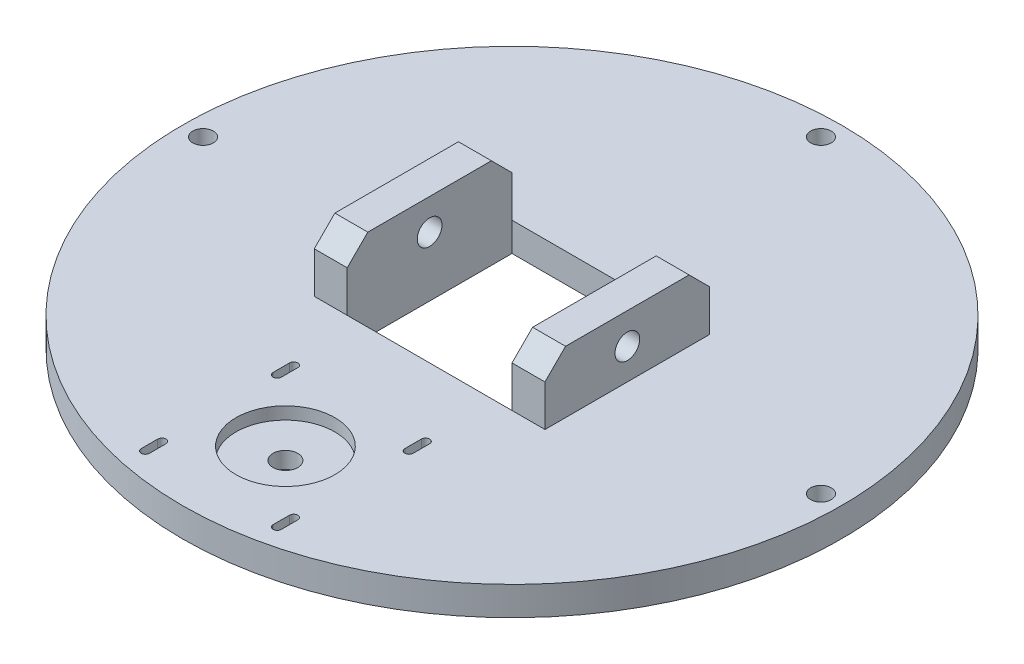
SolidWorks part; units mm, degrees
ref_plane "Front Plane" through (0, 0, 0) normal (0, 0, 1) x (1, 0, 0)
ref_plane "Top Plane" through (0, 0, 0) normal (0, 1, 0) x (1, 0, 0)
ref_plane "Right Plane" through (0, 0, 0) normal (1, 0, 0) x (0, 0, -1)
sketch "Sketch1" plane through (0, 0, 0) normal (0, 1, 0) x (1, 0, 0)
  circle A0 centre (0, 0) radius 80
  dimension "D1" = 160
extrude "Boss-Extrude1" add sketch "Sketch1" along normal blind 7 contours A0
sketch "Sketch2" plane through (0, 7, 0) normal (0, 1, 0) x (1, 0, 0)
  circle A0 centre (0, 0) radius 75 construction
  circle A1 centre (-75, 0) radius 2.5
  circle A2 centre (0, 75) radius 2.5
  circle A3 centre (75, 0) radius 2.5
  point P3 (0, 75)
  point P4 (75, 0)
  point P5 (0, -75)
  point P6 (-75, 0)
  point P7 (-75, 0)
  dimension "D1" = 150
extrude "Cut-Extrude1" cut sketch "Sketch2" against normal up to next
sketch "Sketch3" plane through (0, 7, 0) normal (0, 1, 0) x (1, 0, 0)
  line L1 (-20, 20) -> (20, 20)
  line L2 (-20, 20) -> (-20, -20)
  line L3 (-20, -20) -> (20, -20)
  line L4 (20, 20) -> (20, -20)
  dimension "D1" = 40
  dimension "D2" = 20
  dimension "D3" = 20
extrude "Cut-Extrude2" cut sketch "Sketch3" against normal up to next
sketch "Sketch5" plane through (0, 7, 0) normal (0, 1, 0) x (1, 0, 0)
  line L0 (-20, -20) -> (20, -20) construction
  line L1 (-20, 20) -> (-28, 20)
  line L2 (-20, 20) -> (-20, -20)
  line L3 (-20, -20) -> (-28, -20)
  line L4 (-28, 20) -> (-28, -20)
  dimension "D1" = 8
extrude "Boss-Extrude2" add sketch "Sketch5" along normal blind 15
fillet "Fillet1" radius 5 2 edges at (-24, 22, -20) (-24, 22, 20) profile chamfer
sketch "Sketch6" plane through (-28, 0, 0) normal (-1, 0, 0) x (0, 0, 1)
  line L0 (-15, 22) -> (15, 22) construction
  line L2 (20, 17) -> (20, 7) construction
  circle A0 centre (0, 14.5) radius 3
  dimension "D1" = 6
  dimension "D2" = 7.5
  dimension "D3" = 20
extrude "Cut-Extrude4" cut sketch "Sketch6" against normal up to next
ref_plane "Plane1" [suppressed] through (0, 0, 0) normal (-1, 0, 0) x (0, 0, 1)
mirror "Mirror1" about plane through (0, 0, 0) normal (-1, 0, 0) of "Cut-Extrude4", "Fillet1", "Boss-Extrude2"
sketch "Sketch4" plane through (0, 7, 0) normal (0, 1, 0) x (1, 0, 0)
  line L0 (-16, -41) -> (-16, -37) construction
  line L5 (-21, -34) -> (21, -34) construction
  line L6 (0, 0) -> (0, -80) construction
  line L7 (0, 0) -> (-72.5, 0) construction
  line L8 (-21, -34) -> (-21, -76) construction
  line L23 (-21, -76) -> (21, -76) construction
  line L24 (21, -34) -> (21, -76) construction
  line L27 (-16, -39) -> (16, -39) construction
  line L28 (-16, -39) -> (-16, -71) construction
  line L31 (-16, -71) -> (16, -71) construction
  line L32 (16, -39) -> (16, -71) construction
  line L33 (-17, -41) -> (-17, -37)
  line L34 (-15, -41) -> (-15, -37)
  line L35 (16, -41) -> (16, -37) construction
  line L36 (15, -41) -> (15, -37)
  line L37 (17, -41) -> (17, -37)
  line L38 (16, -73) -> (16, -69) construction
  line L39 (15, -73) -> (15, -69)
  line L40 (17, -73) -> (17, -69)
  line L41 (-16, -73) -> (-16, -69) construction
  line L42 (-17, -73) -> (-17, -69)
  line L43 (-15, -73) -> (-15, -69)
  circle A11 centre (-75, 0) radius 2.5 construction
  arc A22 (-17, -41) -> (-15, -41) centre (-16, -41) ccw
  arc A23 (-15, -37) -> (-17, -37) centre (-16, -37) ccw
  arc A24 (15, -41) -> (17, -41) centre (16, -41) ccw
  arc A25 (17, -37) -> (15, -37) centre (16, -37) ccw
  arc A26 (15, -73) -> (17, -73) centre (16, -73) ccw
  arc A27 (17, -69) -> (15, -69) centre (16, -69) ccw
  arc A28 (-17, -73) -> (-15, -73) centre (-16, -73) ccw
  arc A29 (-15, -69) -> (-17, -69) centre (-16, -69) ccw
  circle A30 centre (0, -55) radius 3
  circle A31 centre (0, 0) radius 80 construction
  point P17 (-16, -39)
  point P26 (16, -39)
  point P33 (16, -71)
  point P42 (-16, -71)
  dimension "D5" = 5
  dimension "D8" = 5
  dimension "D10" = 2
  dimension "D9" = 2
  dimension "D11" = 2
  dimension "D12" = 2
  dimension "D1" = 21
  dimension "D7" = 5
  dimension "D13" = 6
  dimension "D2" = 21
  dimension "D3" = 34
  dimension "D4" = 42
  dimension "D6" = 5
  dimension "D14" = 55
extrude "Cut-Extrude3" cut sketch "Sketch4" against normal up to next
sketch "Sketch7" plane through (0, 0, 0) normal (0, -1, 0) x (1, 0, 0)
  line L0 (-15, 69) -> (-15, 73) construction
  line L1 (-15, 69) -> (-15, 73)
  line L2 (-16, 69) -> (-16, 73) construction
  line L3 (-18.5, 69) -> (-18.5, 73)
  line L4 (-13.5, 69) -> (-13.5, 73)
  line L5 (17, 69) -> (17, 73)
  line L6 (16, 69) -> (16, 73) construction
  line L7 (13.5, 69) -> (13.5, 73)
  line L8 (18.5, 69) -> (18.5, 73)
  line L9 (17, 37) -> (17, 41)
  line L10 (16, 37) -> (16, 41) construction
  line L11 (13.5, 37) -> (13.5, 41)
  line L12 (18.5, 37) -> (18.5, 41)
  line L13 (-15, 37) -> (-15, 41)
  line L14 (-16, 37) -> (-16, 41) construction
  line L15 (-18.5, 37) -> (-18.5, 41)
  line L16 (-13.5, 37) -> (-13.5, 41)
  arc A0 (-15, 73) -> (-17, 73) centre (-16, 73) ccw construction
  arc A1 (-15, 73) -> (-17, 73) centre (-16, 73) ccw
  arc A2 (-18.5, 69) -> (-13.5, 69) centre (-16, 69) ccw
  arc A3 (-13.5, 73) -> (-18.5, 73) centre (-16, 73) ccw
  arc A4 (17, 73) -> (15, 73) centre (16, 73) ccw
  arc A5 (13.5, 69) -> (18.5, 69) centre (16, 69) ccw
  arc A6 (18.5, 73) -> (13.5, 73) centre (16, 73) ccw
  arc A7 (17, 41) -> (15, 41) centre (16, 41) ccw
  arc A8 (13.5, 37) -> (18.5, 37) centre (16, 37) ccw
  arc A9 (18.5, 41) -> (13.5, 41) centre (16, 41) ccw
  arc A10 (-15, 41) -> (-17, 41) centre (-16, 41) ccw
  arc A11 (-18.5, 37) -> (-13.5, 37) centre (-16, 37) ccw
  arc A12 (-13.5, 41) -> (-18.5, 41) centre (-16, 41) ccw
  point P5 (-16, 71)
  point P17 (16, 71)
  point P27 (16, 39)
  point P37 (-16, 39)
  line M5 (15, 37) -> (15, 41)
  arc M6 (15, 41) -> (17, 41) centre (16, 41) cw
  line M7 (17, 41) -> (17, 37)
  arc M8 (17, 37) -> (15, 37) centre (16, 37) cw
  line M9 (-17, 37) -> (-17, 41)
  arc M10 (-17, 41) -> (-15, 41) centre (-16, 41) cw
  line M11 (-15, 41) -> (-15, 37)
  arc M12 (-15, 37) -> (-17, 37) centre (-16, 37) cw
  line M13 (-17, 69) -> (-17, 73)
  arc M14 (-17, 73) -> (-15, 73) centre (-16, 73) cw
  line M15 (-15, 73) -> (-15, 69)
  arc M16 (-15, 69) -> (-17, 69) centre (-16, 69) cw
  line M17 (15, 69) -> (15, 73)
  arc M18 (15, 73) -> (17, 73) centre (16, 73) cw
  line M19 (17, 73) -> (17, 69)
  arc M20 (17, 69) -> (15, 69) centre (16, 69) cw
  dimension "D1" = 2.5
  dimension "D2" = 2
  dimension "D3" = 2
  dimension "D4" = 2
extrude "Cut-Extrude5" cut sketch "Sketch7" against normal blind 2 contours L4 A3 L3 A2 M16 M13 M14 M15 | L8 A6 L7 A5 M20 M17 M18 M19 | L16 A12 L15 A11 M12 M9 M10 M11 | L12 A9 L11 A8 M8 M5 M6 M7
sketch "Sketch8" plane through (0, 7, 0) normal (0, 1, 0) x (1, 0, 0)
  line L0 (0, 0) -> (0, -55) construction
  line L1 (0, 0) -> (75, 0) construction
  circle A0 centre (0, -55) radius 12
  dimension "D1" = 55
  dimension "D2" = 24
extrude "Cut-Extrude6" cut sketch "Sketch8" against normal blind 3
